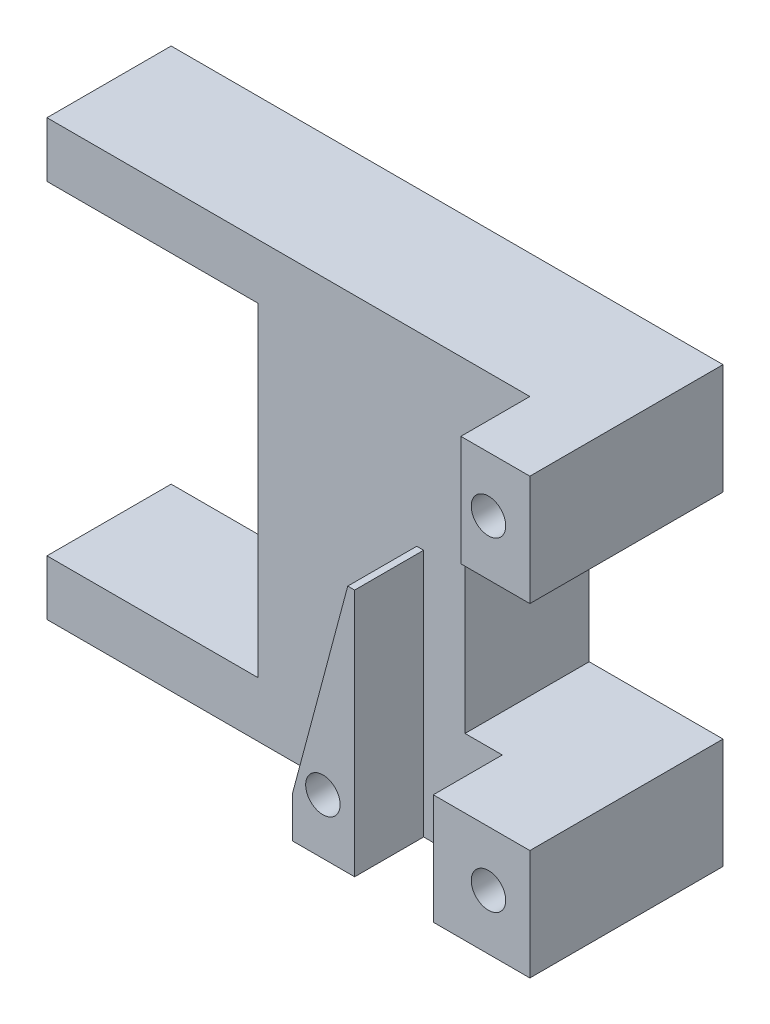
SolidWorks part; units mm, degrees
ref_plane "Front Plane" through (0, 0, 0) normal (0, 0, 1) x (1, 0, 0)
ref_plane "Top Plane" through (0, 0, 0) normal (0, 1, 0) x (1, 0, 0)
ref_plane "Right Plane" through (0, 0, 0) normal (1, 0, 0) x (0, 0, -1)
sketch "Sketch1" plane through (0, 0, 0) normal (0, 0, 1) x (-1, 0, 0)
  line L0 (-12.7933, 22.7933) -> (-12.7933, -0.7067)
  line L1 (2.5067, -4.7067) -> (-37.4933, -4.7067)
  line L2 (2.5067, -4.7067) -> (2.5067, -0.7067)
  line L3 (2.5067, -0.7067) -> (-37.4933, -0.7067)
  line L4 (-37.4933, -4.7067) -> (-37.4933, -0.7067)
  line L5 (2.5067, 26.7933) -> (-37.4933, 26.7933)
  line L6 (2.5067, 26.7933) -> (2.5067, 22.7933)
  line L7 (2.5067, 22.7933) -> (-37.4933, 22.7933)
  line L8 (-37.4933, 26.7933) -> (-37.4933, 22.7933)
  line L9 (-2.4024, 24.2995) -> (-2.5192, -3.3258)
  line L10 (-37.4933, 22.7933) -> (-37.4933, -0.7067)
  line L11 (-27.7933, 22.7933) -> (-27.7933, -0.7067)
  line L12 (-20.2933, 54.7933) -> (-20.2933, -7.7067)
  line L13 (-37.4933, 18.7933) -> (-27.7933, 18.7933)
  line L14 (-37.4933, 3.2933) -> (-27.7933, 3.2933)
  arc A0 (-15.2933, 49.7933) -> (-25.2933, 49.7933) centre (-20.2933, 49.7933) ccw construction
  dimension "D1" = 4
  dimension "D2" = 40
  dimension "D3" = 4
  dimension "D4" = 23.5
  dimension "D5" = 7.5
  dimension "D6" = 7.5
  dimension "D7" = 8
  dimension "D8" = 8
extrude "Boss-Extrude1" add sketch "Sketch1" along normal blind 9
sketch "Sketch2" plane through (0, 0, 9) normal (0, 0, 1) x (1, 0, 0)
  line L0 (37.4933, -18.7933) -> (27.7933, -18.7933) construction
  line L1 (37.4933, -26.7933) -> (30.4933, -26.7933)
  line L2 (37.4933, -26.7933) -> (37.4933, -18.7933)
  line L3 (37.4933, -18.7933) -> (30.4933, -18.7933)
  line L4 (30.4933, -26.7933) -> (30.4933, -18.7933)
  line L5 (-2.5067, 4.7067) -> (37.4933, 4.7067) construction
  line L10 (20.2933, -54.7933) -> (20.2933, -26.7933)
  line L11 (-2.5067, -26.7933) -> (37.4933, -26.7933) construction
  line L12 (20.2933, -26.7933) -> (20.2933, 4.7067)
  line L14 (37.4933, -3.2933) -> (27.7933, -3.2933) construction
  line L17 (37.4933, 4.7067) -> (32.4933, 4.7067)
  line L18 (24.7933, -26.7933) -> (20.2933, -26.7933)
  line L19 (24.7933, -26.7933) -> (24.7933, -8.7933)
  line L20 (24.7933, -8.7933) -> (20.2933, -8.7933)
  line L21 (20.2933, -26.7933) -> (20.2933, -8.7933)
  line L22 (37.4933, 4.7067) -> (37.4933, -3.2933)
  line L23 (37.4933, -3.2933) -> (32.4933, -3.2933)
  line L24 (32.4933, 4.7067) -> (32.4933, -3.2933)
  arc A0 (15.2933, -49.7933) -> (25.2933, -49.7933) centre (20.2933, -49.7933) ccw construction
  line M18 (-2.5067, -26.7933) -> (37.4933, -26.7933)
  line M19 (37.4933, -26.7933) -> (37.4933, -18.7933)
  line M20 (12.7933, -22.7933) -> (-2.5067, -22.7933)
  line M22 (-2.5067, 0.7067) -> (12.7933, 0.7067)
  line M23 (37.4933, -3.2933) -> (37.4933, 4.7067)
  line M24 (37.4933, 4.7067) -> (-2.5067, 4.7067)
  dimension "D1" = 4.5
  dimension "D2" = 5
  dimension "D3" = 18
  dimension "D4" = 7
extrude "Boss-Extrude2" add sketch "Sketch2" along normal blind 5 contours L4 M18 M19 M20 | L19 L20 L12 M18 | L24 M22 M23 M24
chamfer "Chamfer1" distance 4 distance2 15 1 edges at (20.2933, -8.7933, 11.5)
sketch "Sketch4" plane through (0, 0, 14) normal (0, 0, 1) x (1, 0, 0)
  line L0 (37.4933, -26.7933) -> (37.4933, -18.7933) construction
  line L1 (37.4933, -3.2933) -> (37.4933, 4.7067) construction
  circle A0 centre (34.4933, -22.7933) radius 1.25
  circle A1 centre (34.4933, 0.7067) radius 1.25
  circle A2 centre (22.4933, -22.7933) radius 1.25
  point P8 (37.4933, 0.7067)
  point P9 (37.4933, -22.7933)
  dimension "D1" = 2.5
  dimension "D2" = 2.5
  dimension "D5" = 2.5
  dimension "D3" = 3
  dimension "D4" = 3
  dimension "D6" = 12
extrude "Cut-Extrude1" cut sketch "Sketch4" against normal blind 5
sketch "Sketch6" plane through (0, 0, 0) normal (0, 0, -1) x (-1, 0, 0)
  line L0 (-20.2933, -54.7933) -> (-20.2933, 7.7067)
  line L1 (2.5067, -26.7933) -> (-37.4933, -26.7933) construction
  line L2 (-25.2933, -1.7933) -> (-15.2933, -1.7933) construction
  line L3 (-25.2933, -1.7933) -> (-25.2933, -21.7933) construction
  line L4 (-25.2933, -21.7933) -> (-15.2933, -21.7933) construction
  line L5 (-15.2933, -1.7933) -> (-15.2933, -21.7933) construction
  arc A0 (-25.2933, -49.7933) -> (-15.2933, -49.7933) centre (-20.2933, -49.7933) ccw construction
  circle A1 centre (-25.2933, -1.7933) radius 1.25
  circle A2 centre (-15.2933, -1.7933) radius 1.25
  circle A3 centre (-15.2933, -21.7933) radius 1.25
  circle A4 centre (-25.2933, -21.7933) radius 1.25
  point P10 (-20.2933, -1.7933)
  dimension "D4" = 2.5
  dimension "D5" = 2.5
  dimension "D6" = 2.5
  dimension "D7" = 2.5
  dimension "D1" = 10
  dimension "D2" = 20
  dimension "D3" = 5
extrude "Cut-Extrude2" cut sketch "Sketch6" against normal blind 5 contours A1 | A2 | A3 | A4
